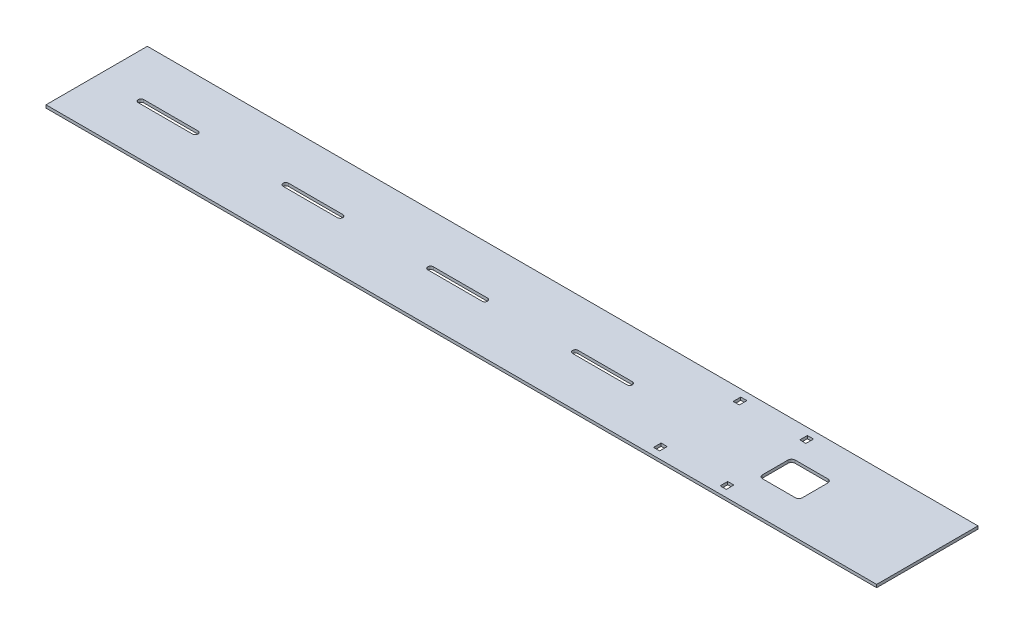
SolidWorks part; units mm, degrees
material "Q355"
ref_plane "前视基准面" through (0, 0, 0) normal (0, 0, 1) x (1, 0, 0)
ref_plane "上视基准面" through (0, 0, 0) normal (0, 1, 0) x (1, 0, 0)
ref_plane "右视基准面" through (0, 0, 0) normal (1, 0, 0) x (0, 0, -1)
sketch "草图1" plane through (0, 0, 0) normal (0, 1, 0) x (1, 0, 0)
  line L0 (-1147.5, 0) -> (1147.5, 0) construction
  line L1 (-1147.5, 140) -> (1147.5, 140)
  line L2 (-1147.5, 140) -> (-1147.5, -140)
  line L3 (-1147.5, -140) -> (1147.5, -140)
  line L4 (1147.5, 140) -> (1147.5, -140)
  line L5 (-1147.5, 140) -> (1147.5, -140) construction
  line L6 (-1147.5, -140) -> (1147.5, 140) construction
  point P0 (0, 0)
  dimension "D1" = 280
  dimension "D2" = 2295
extrude "凸台-拉伸1" add sketch "草图1" along normal blind 8
sketch "草图2" plane through (0, 8, 0) normal (0, 1, 0) x (1, 0, 0)
  line L0 (-1147.5, 0) -> (1147.5, 0) construction
  line L1 (-1147.5, 140) -> (-1147.5, -140) construction
  line L2 (1147.5, -140) -> (1147.5, 140) construction
  line L3 (-1025, 0) -> (-875, 0) construction
  line L4 (-1025, 7.5) -> (-875, 7.5)
  line L5 (-1025, -7.5) -> (-875, -7.5)
  arc A0 (-1025, 7.5) -> (-1025, -7.5) centre (-1025, 0) ccw
  arc A1 (-875, -7.5) -> (-875, 7.5) centre (-875, 0) ccw
  point P5 (-950, 0)
  dimension "D1" = 7.5
  dimension "D2" = 122.5
  dimension "D3" = 150
extrude "切除-拉伸1" cut sketch "草图2" against normal blind 8
pattern_linear "阵列(线性)1" count 4 spacing 400 along (1, 0, 0) of "切除-拉伸1"
sketch "草图3" plane through (0, 8, 0) normal (0, 1, 0) x (1, 0, 0)
  line L0 (1147.5, 0) -> (-1025, 0) construction
  line L1 (727.5, 45) -> (837.5, 45)
  line L2 (727.5, 45) -> (727.5, -45)
  line L3 (727.5, -45) -> (837.5, -45)
  line L4 (837.5, 45) -> (837.5, -45)
  line L5 (727.5, 45) -> (837.5, -45) construction
  line L6 (727.5, -45) -> (837.5, 45) construction
  line L7 (1147.5, -140) -> (1147.5, 140) construction
  line L8 (1147.5, -140) -> (1147.5, 140) construction
  point P0 (782.5, 0)
  dimension "D1" = 110
  dimension "D2" = 90
  dimension "D3" = 310
extrude "切除-拉伸2" cut sketch "草图3" against normal blind 8
sketch "草图4" plane through (0, 8, 0) normal (0, 1, 0) x (1, 0, 0)
  line L0 (1147.5, -140) -> (1147.5, 140) construction
  line L1 (695.5, -120.5) -> (712.5, -120.5)
  line L2 (695.5, -120.5) -> (695.5, -99.5)
  line L3 (695.5, -99.5) -> (712.5, -99.5)
  line L4 (712.5, -120.5) -> (712.5, -99.5)
  line L5 (695.5, -120.5) -> (712.5, -99.5) construction
  line L6 (695.5, -99.5) -> (712.5, -120.5) construction
  line L7 (-1147.5, -140) -> (1147.5, -140) construction
  line L8 (511.5, -120.5) -> (528.5, -120.5)
  line L9 (511.5, -120.5) -> (511.5, -99.5)
  line L10 (511.5, -99.5) -> (528.5, -99.5)
  line L11 (528.5, -120.5) -> (528.5, -99.5)
  line L12 (511.5, -120.5) -> (528.5, -99.5) construction
  line L13 (511.5, -99.5) -> (528.5, -120.5) construction
  line L14 (511.5, 99.5) -> (528.5, 99.5)
  line L15 (511.5, 99.5) -> (511.5, 120.5)
  line L16 (511.5, 120.5) -> (528.5, 120.5)
  line L17 (528.5, 99.5) -> (528.5, 120.5)
  line L18 (511.5, 99.5) -> (528.5, 120.5) construction
  line L19 (511.5, 120.5) -> (528.5, 99.5) construction
  line L20 (695.5, 99.5) -> (712.5, 99.5)
  line L21 (695.5, 99.5) -> (695.5, 120.5)
  line L22 (695.5, 120.5) -> (712.5, 120.5)
  line L23 (712.5, 99.5) -> (712.5, 120.5)
  line L24 (695.5, 99.5) -> (712.5, 120.5) construction
  line L25 (695.5, 120.5) -> (712.5, 99.5) construction
  point P0 (704, -110)
  point P12 (520, -110)
  point P17 (520, 110)
  point P22 (704, 110)
  dimension "D1" = 17
  dimension "D2" = 21
  dimension "D3" = 435
  dimension "D4" = 19.5
  dimension "D7" = 184
  dimension "D8" = 220
  dimension "D5" = 2
  dimension "D6" = 2
extrude "切除-拉伸3" cut sketch "草图4" against normal blind 8
fillet "圆角1" radius 10 4 edges at (837.5, 4, -45) (727.5, 4, -45) (837.5, 4, 45) (727.5, 4, 45)
